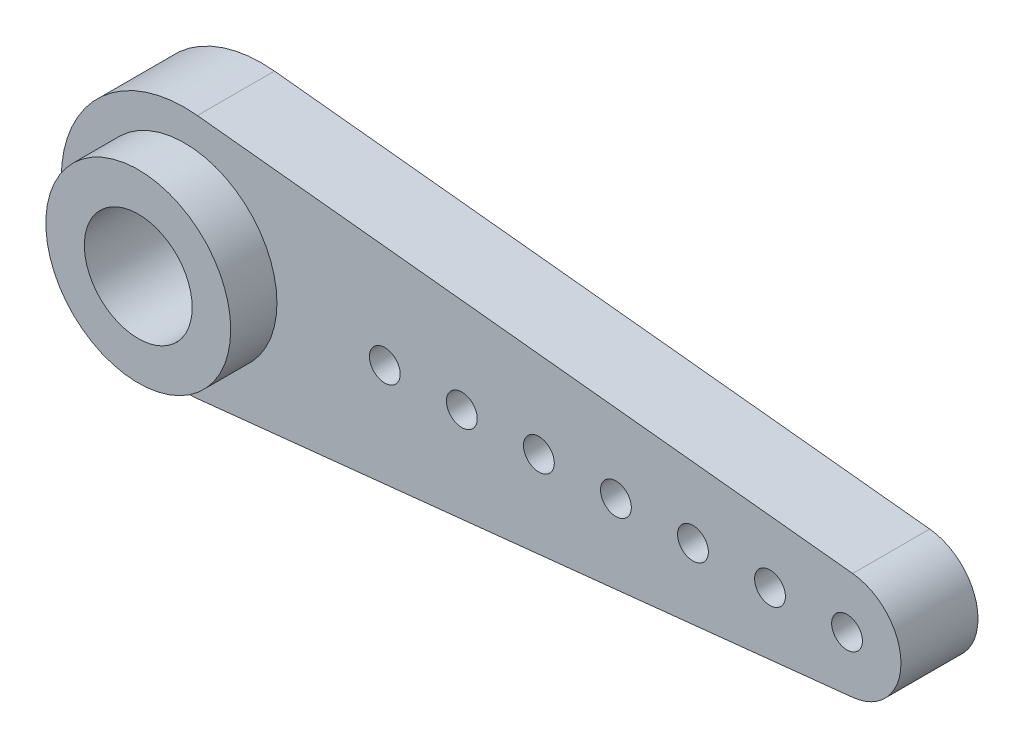
SolidWorks part; units mm, degrees
material "PVC rigide"
ref_plane "Plan de face" through (0, 0, 0) normal (0, 0, 1) x (1, 0, 0)
ref_plane "Plan de dessus" through (0, 0, 0) normal (0, 1, 0) x (1, 0, 0)
ref_plane "Plan de droite" through (0, 0, 0) normal (1, 0, 0) x (0, 0, -1)
sketch "Esquisse1" plane through (0, 0, 0) normal (0, 0, 1) x (1, 0, 0)
  line L0 (0.8372, 7.9561) -> (43.3663, 3.4808)
  line L1 (0.8372, -7.9561) -> (43.3663, -3.4808)
  arc A0 (0.8372, 7.9561) -> (0.8372, -7.9561) centre (0, 0) ccw
  arc A1 (43.3663, -3.4808) -> (43.3663, 3.4808) centre (43, 0) ccw
  circle A2 centre (43, 0) radius 1
  circle A3 centre (0, 0) radius 1.5
  circle A4 centre (38, 0) radius 1
  circle A5 centre (33, 0) radius 1
  circle A6 centre (28, 0) radius 1
  circle A7 centre (23, 0) radius 1
  circle A8 centre (18, 0) radius 1
  circle A9 centre (13, 0) radius 1
  dimension "D1" = 3
  dimension "D2" = 2
  dimension "D3" = 3.5
  dimension "D4" = 8
  dimension "D5" = 43
  dimension "D6" = 7
  dimension "D7" = 30
extrude "Boss.-Extru.1" add sketch "Esquisse1" along normal blind 5
sketch "Esquisse2" plane through (0, 0, 5) normal (0, 0, 1) x (1, 0, 0)
  circle A0 centre (0, 0) radius 6
  dimension "D1" = 12
extrude "Boss.-Extru.2" add sketch "Esquisse2" along normal blind 3
sketch "Esquisse3" plane through (0, 0, 8) normal (0, 0, 1) x (1, 0, 0)
  circle A0 centre (0, 0) radius 3.5
  dimension "D1" = 7
extrude "Enlèv. mat.-Extru.1" cut sketch "Esquisse3" against normal blind 5
